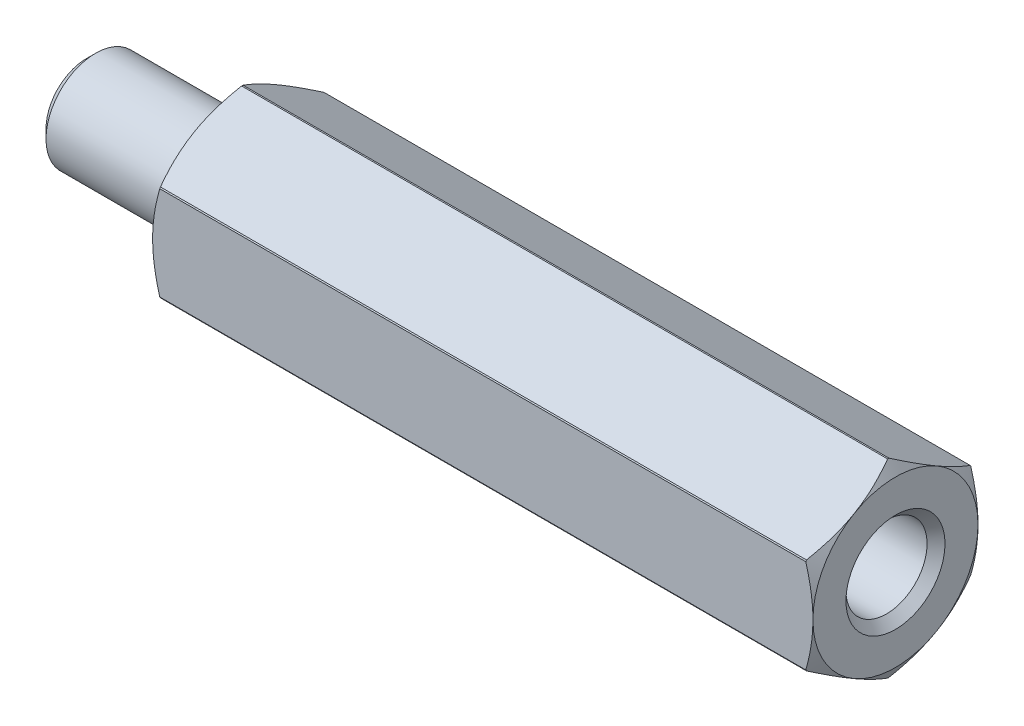
SolidWorks part; units mm, degrees
ref_plane "Front Plane" through (0, 0, 0) normal (0, 0, 1) x (1, 0, 0)
ref_plane "Top Plane" through (0, 0, 0) normal (0, 1, 0) x (1, 0, 0)
ref_plane "Right Plane" through (0, 0, 0) normal (1, 0, 0) x (0, 0, -1)
sketch "Sketch1" plane through (0, 0, 0) normal (0, 0, 1) x (1, 0, 0)
  line L0 (0, 0) -> (0, 5)
  line L1 (0, 5) -> (0.433, 5.75)
  line L2 (0.433, 5.75) -> (39.567, 5.75)
  line L3 (39.567, 5.75) -> (40, 5)
  line L4 (40, 5) -> (40, 0)
  line L5 (40, 0) -> (0, 0)
  line L6 (40, 0) -> (0, 0) construction
revolve "Revolve1" add sketch "Sketch1" angle 360 about L6
sketch "Sketch2" plane through (0, 0, 0) normal (1, 0, 0) x (0, 0, -1)
  line L0 (-10, 10) -> (-10, -10)
  line L1 (-10, -10) -> (10, -10)
  line L2 (10, -10) -> (10, 10)
  line L3 (10, 10) -> (-10, 10)
  line L4 (-5, 2.8868) -> (-5, -2.8868)
  line L5 (-5, -2.8868) -> (0, -5.7735)
  line L6 (0, -5.7735) -> (5, -2.8868)
  line L7 (5, -2.8868) -> (5, 2.8868)
  line L8 (5, 2.8868) -> (0, 5.7735)
  line L9 (0, 5.7735) -> (-5, 2.8868)
extrude "Cut-Extrude1" cut sketch "Sketch2" along normal blind 40
sketch "Sketch3" plane through (0, 0, 0) normal (0, 0, 1) x (1, 0, 0)
  line L0 (25.6, 0) -> (27.0194, 2.4585)
  line L1 (27.0194, 2.4585) -> (39.4585, 2.4585)
  line L2 (39.4585, 2.4585) -> (40, 3)
  line L3 (40, 3) -> (40, 0)
  line L4 (40, 0) -> (25.6, 0)
  line L5 (40, 0) -> (25.6, 0) construction
revolve "Cut-Revolve1" cut sketch "Sketch3" angle 360 about L5
cosmetic thread "Cosmetic Thread1" parameters "D1"=12, "D2"=6
sketch "Sketch4" plane through (0, 0, 0) normal (0, 0, 1) x (1, 0, 0)
  line L0 (-9, 0) -> (-9, 2.4585)
  line L1 (-9, 2.4585) -> (-8.4585, 3)
  line L2 (-8.4585, 3) -> (-0.9, 3)
  line L3 (-0.9, 3) -> (-0.9, 2.4585)
  line L4 (-0.9, 2.4585) -> (0, 2.4585)
  line L5 (0, 2.4585) -> (0, 0)
  line L6 (0, 0) -> (-9, 0)
  line L7 (0, 0) -> (-9, 0) construction
revolve "Revolve2" add sketch "Sketch4" angle 360 about L7
cosmetic thread "Cosmetic Thread2" parameters "D1"=8.1, "D2"=4.917
